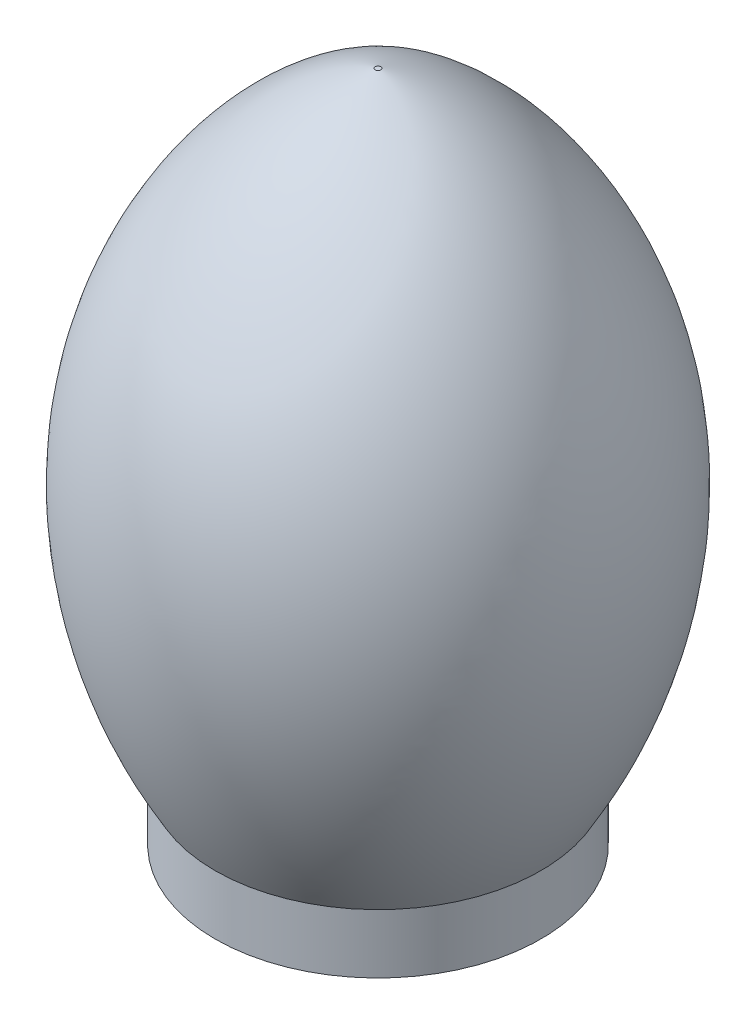
SolidWorks part; units mm, degrees
ref_plane "Front Plane" through (0, 0, 0) normal (0, 0, 1) x (1, 0, 0)
ref_plane "Top Plane" through (0, 0, 0) normal (0, 1, 0) x (1, 0, 0)
ref_plane "Right Plane" through (0, 0, 0) normal (1, 0, 0) x (0, 0, -1)
sketch "Sketch3" plane through (0, -67.0312, 0) normal (1, 0, 0) x (0, 0, -1)
  line L0 (0, -86.409) -> (45.0343, -86.409)
  line L1 (-1.7336, -89.409) -> (45.0343, -89.409)
  line L2 (45.0343, 83.8246) -> (45.0343, 86.7153)
  line L3 (45.0343, 86.7153) -> (44.232, 86.7153)
  line L4 (45.0343, -86.409) -> (45.0343, -89.409)
  line L5 (45.0343, 83.8246) -> (45.0343, -86.409)
  spline S0 degree 3 poles (0, -86.409) (-19.811, -52.0343) (-30.029, 18.5668) (19.0108, 76.6016) (45.0343, 83.8246) knots 0 0 0 0 0.591831 1 1 1 1
  spline S1 degree 1 poles (-1.7336, -89.409) (44.232, 86.7153) knots 0 0 1 1 construction
  spline S2 degree 3 poles (-1.7336, -89.409) (-1.9974, -88.9513) (-2.5217, -88.0438) (-3.5962, -86.1662) (-5.4085, -82.8673) (-8.8314, -76.153) (-13.0915, -66.2897) (-17.156, -54.0931) (-21.1045, -37.4673) (-23.1522, -16.2151) (-20.9858, 5.0892) (-16.5139, 21.7952) (-10.1294, 38.1803) (-0.9179, 53.6673) (10.8076, 66.9789) (20.7951, 75.5554) (30.0609, 81.2504) (37.9888, 84.7558) (42.135, 86.1332) (44.232, 86.7153) knots -0.00862 -0.00862 -0.00862 -0.00862 -0.00074 0.00714 0.022899 0.054419 0.117458 0.180496 0.243535 0.369613 0.49569 0.558729 0.621768 0.747845 0.810884 0.873923 0.936961 0.968481 1 1 1 1
  dimension "D1" = 3
revolve "Revolve2" add sketch "Sketch3" angle 360 about L5
sketch "Sketch6" plane through (0, -156.4402, 0) normal (0, -1, 0) x (1, 0, 0)
  circle A1 centre (0, -45.0343) radius 46.7679
extrude "Boss-Extrude1" add sketch "Sketch6" along normal blind 17
